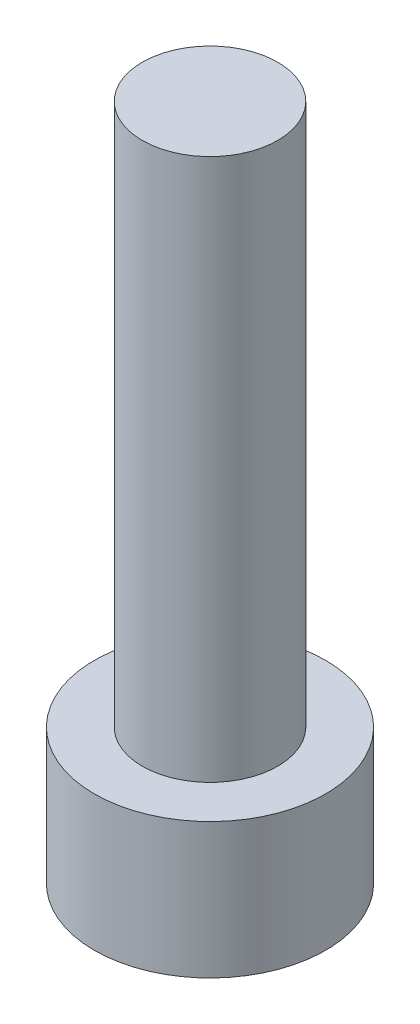
SolidWorks part; units mm, degrees
ref_plane "Front Plane" through (0, 0, 0) normal (0, 0, 1) x (1, 0, 0)
ref_plane "Top Plane" through (0, 0, 0) normal (0, 1, 0) x (1, 0, 0)
ref_plane "Right Plane" through (0, 0, 0) normal (1, 0, 0) x (0, 0, -1)
sketch "Sketch1" plane through (0, 0, 0) normal (0, 1, 0) x (1, 0, 0)
  circle A0 centre (0, 0) radius 3.415
  dimension "D1" = 6.83
extrude "Boss-Extrude1" add sketch "Sketch1" along normal blind 4
sketch "Sketch2" plane through (0, 4, 0) normal (0, 1, 0) x (1, 0, 0)
  circle A0 centre (0, 0) radius 2
  dimension "D1" = 4
extrude "Boss-Extrude2" add sketch "Sketch2" along normal blind 16
